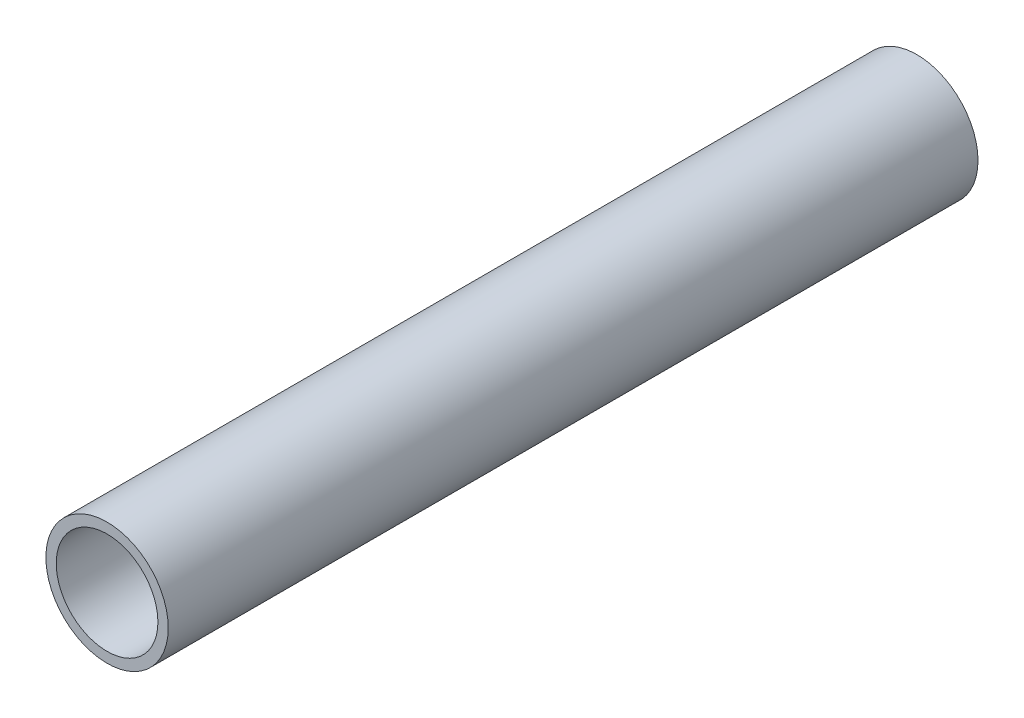
SolidWorks part; units mm, degrees
ref_plane "Front" through (0, 0, 0) normal (0, 0, 1) x (1, 0, 0)
ref_plane "Top" through (0, 0, 0) normal (0, 1, 0) x (1, 0, 0)
ref_plane "Right" through (0, 0, 0) normal (1, 0, 0) x (0, 0, -1)
sketch "Sketch1" plane through (0, 0, 0) normal (0, 0, 1) x (1, 0, 0)
  circle A0 centre (0, 0) radius 4.7498
  circle A1 centre (0, 0) radius 5.715
extrude "Boss-Extrude1" add sketch "Sketch1" along normal blind 75.6412
